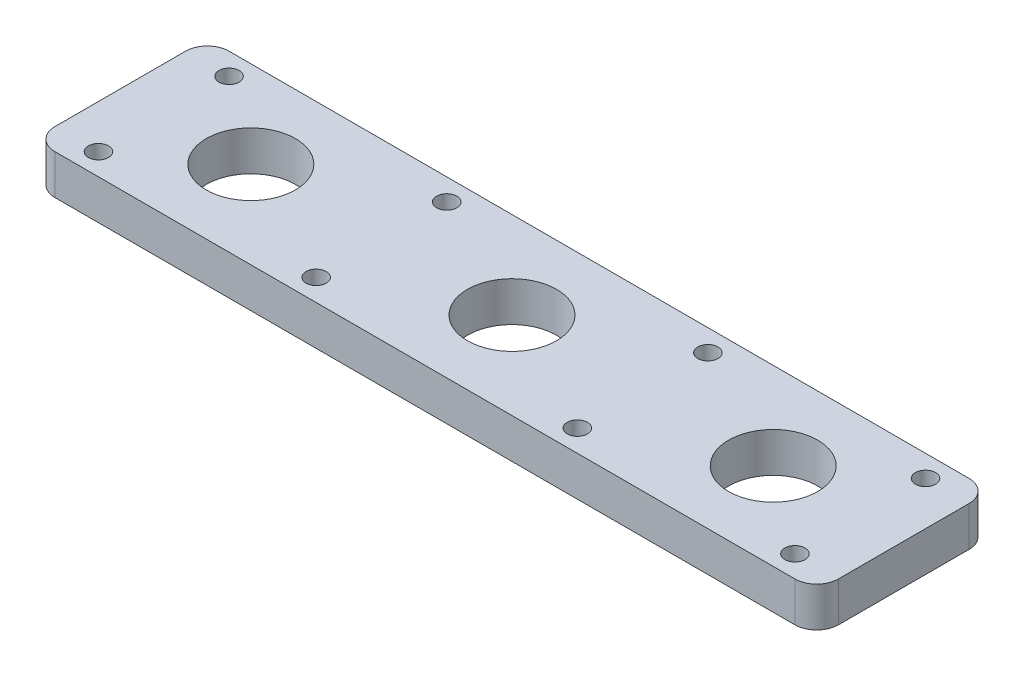
SolidWorks part; units mm, degrees
material "Acrylic (Medium-high impact)"
ref_plane "Front Plane" through (0, 0, 0) normal (0, 0, 1) x (1, 0, 0)
ref_plane "Top Plane" through (0, 0, 0) normal (0, 1, 0) x (1, 0, 0)
ref_plane "Right Plane" through (0, 0, 0) normal (1, 0, 0) x (0, 0, -1)
sketch "Sketch1" plane through (0, 0, 0) normal (0, 1, 0) x (1, 0, 0)
  line L0 (-95.25, 12.7) -> (-57.15, 12.7) construction
  line L1 (0, 0) -> (-114.3, 0)
  line L2 (0, 0) -> (0, 25.4)
  line L3 (0, 25.4) -> (-114.3, 25.4)
  line L4 (-114.3, 0) -> (-114.3, 25.4)
  line L5 (-57.15, 12.7) -> (-19.05, 12.7) construction
  line L6 (-57.15, 25.4) -> (-57.15, 12.7) construction
  line L7 (-57.15, 12.7) -> (-57.15, 0) construction
  circle A0 centre (-95.25, 12.7) radius 6.5
  circle A1 centre (-57.15, 12.7) radius 6.5
  circle A2 centre (-19.05, 12.7) radius 6.5
  dimension "D1" = 13
  dimension "D2" = 38.1
  dimension "D3" = 114.3
  dimension "D4" = 25.4
extrude "Boss-Extrude1" add sketch "Sketch1" along normal blind 5.8
hole_wizard "#4 Clearance Hole1" positions "Sketch3" profile "Sketch2" hole size "#4" standard "Ansi Inch" end condition through all
sketch "Sketch3" plane through (0, 5.8, 0) normal (0, 1, 0) x (-1, 0, 0)
  line L2 (57.15, 0) -> (57.15, -25.4) construction
  line L3 (0, -25.4) -> (114.3, -25.4) construction
  line L5 (57.15, -12.7) -> (107.95, -12.7) construction
  line L7 (114.3, 0) -> (0, 0) construction
  line L8 (76.2, -12.7) -> (76.2, -22.225) construction
  line L10 (76.2, -12.7) -> (76.2, -3.175) construction
  line L12 (107.95, -22.225) -> (107.95, -12.7) construction
  line L13 (107.95, -12.7) -> (107.95, -3.175) construction
  line L16 (6.35, -12.7) -> (6.35, -3.175) construction
  line L17 (6.35, -22.225) -> (6.35, -12.7) construction
  line L18 (38.1, -12.7) -> (38.1, -3.175) construction
  line L19 (38.1, -12.7) -> (38.1, -22.225) construction
  circle A0 centre (95.25, -12.7) radius 6.5 construction
  point P32 (107.95, -22.225)
  point P34 (107.95, -3.175)
  point P49 (76.2, -22.225)
  point P51 (76.2, -3.175)
  point P68 (6.35, -22.225)
  point P70 (38.1, -22.225)
  point P72 (38.1, -3.175)
  point P74 (6.35, -3.175)
  dimension "D1" = 9.525
  dimension "D2" = 12.7
  dimension "D3" = 19.05
sketch "Sketch2" plane through (-107.95, 5.8, -22.225) normal (1, 0, 0) x (0, 0, 1)
  line L0 (0, 0) -> (0, 5.8)
  line L1 (0, 5.8) -> (1.4732, 5.8)
  line L2 (1.4732, 5.8) -> (1.4732, 0)
  line L5 (1.4732, 0) -> (0, 0)
  line L11 (0, -6.35) -> (0, 107.95) construction
  dimension "Thru Hole Dia." = 2.9464
  dimension "Thru Hole Depth" = 5.8
fillet "Fillet1" radius 3.175 4 edges at (0, 2.9, 0) (0, 2.9, -25.4) (-114.3, 2.9, 0) (-114.3, 2.9, -25.4)
